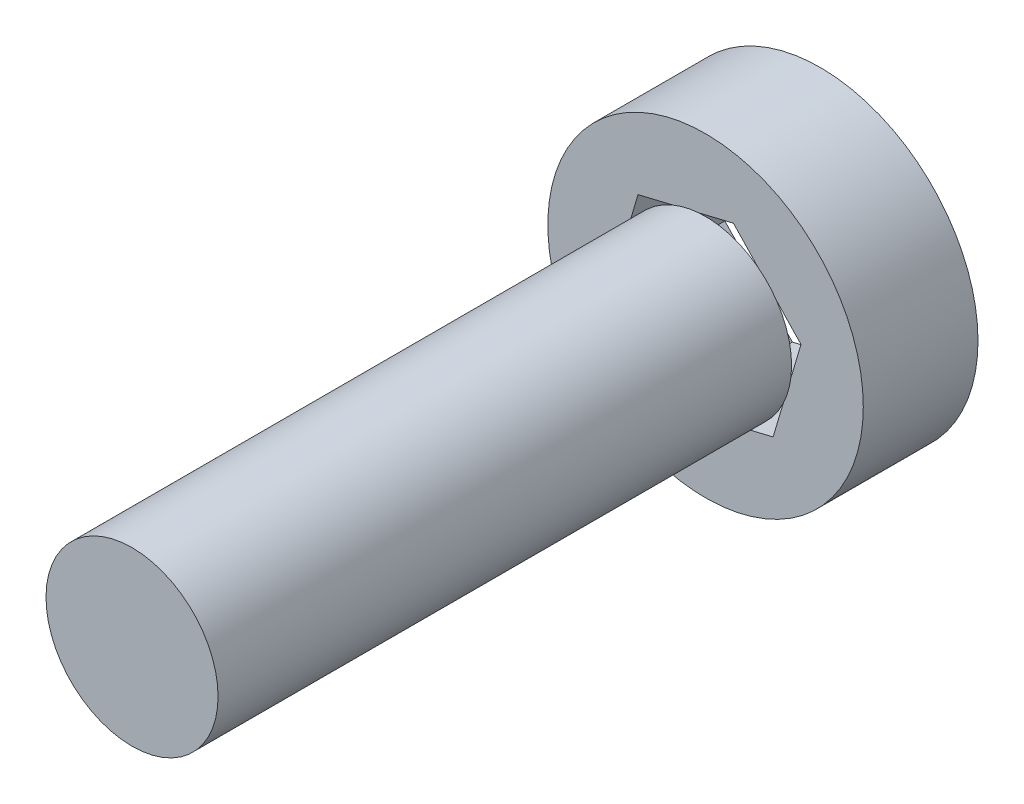
SolidWorks part; units mm, degrees
material "AISI 304"
ref_plane "正面" through (0, 0, 0) normal (0, 0, 1) x (1, 0, 0)
ref_plane "平面" through (0, 0, 0) normal (0, 1, 0) x (1, 0, 0)
ref_plane "右側面" through (0, 0, 0) normal (1, 0, 0) x (0, 0, -1)
sketch "ｽｹｯﾁ1" plane through (0, 0, 0) normal (0, 0, 1) x (1, 0, 0)
  circle A0 centre (0, 0) radius 2.75
  dimension "D1" = 5.5
extrude "ﾎﾞｽ - 押し出し1" add sketch "ｽｹｯﾁ1" along normal blind 2
sketch "ｽｹｯﾁ2" plane through (0, 0, 2) normal (0, 0, 1) x (1, 0, 0)
  circle A0 centre (0, 0) radius 1.5
  dimension "D1" = 3
extrude "ﾎﾞｽ - 押し出し2" add sketch "ｽｹｯﾁ2" along normal blind 10
cosmetic thread "ねじ山1" parameters "D2"=3
sketch "ｽｹｯﾁ3" plane through (0, 0, 0) normal (0, 0, -1) x (-1, 0, 0)
  line L1 (1.6636, -0.3991) -> (1.1774, 1.2412)
  line L2 (1.1774, 1.2412) -> (-0.4862, 1.6403)
  line L3 (-0.4862, 1.6403) -> (-1.6636, 0.3991)
  line L4 (-1.6636, 0.3991) -> (-1.1774, -1.2412)
  line L5 (-1.1774, -1.2412) -> (0.4862, -1.6403)
  line L6 (0.4862, -1.6403) -> (1.6636, -0.3991)
  circle A0 centre (0, 0) radius 1.4816 construction
extrude "ｶｯﾄ - 押し出し1" cut sketch "ｽｹｯﾁ3" against normal blind 2
